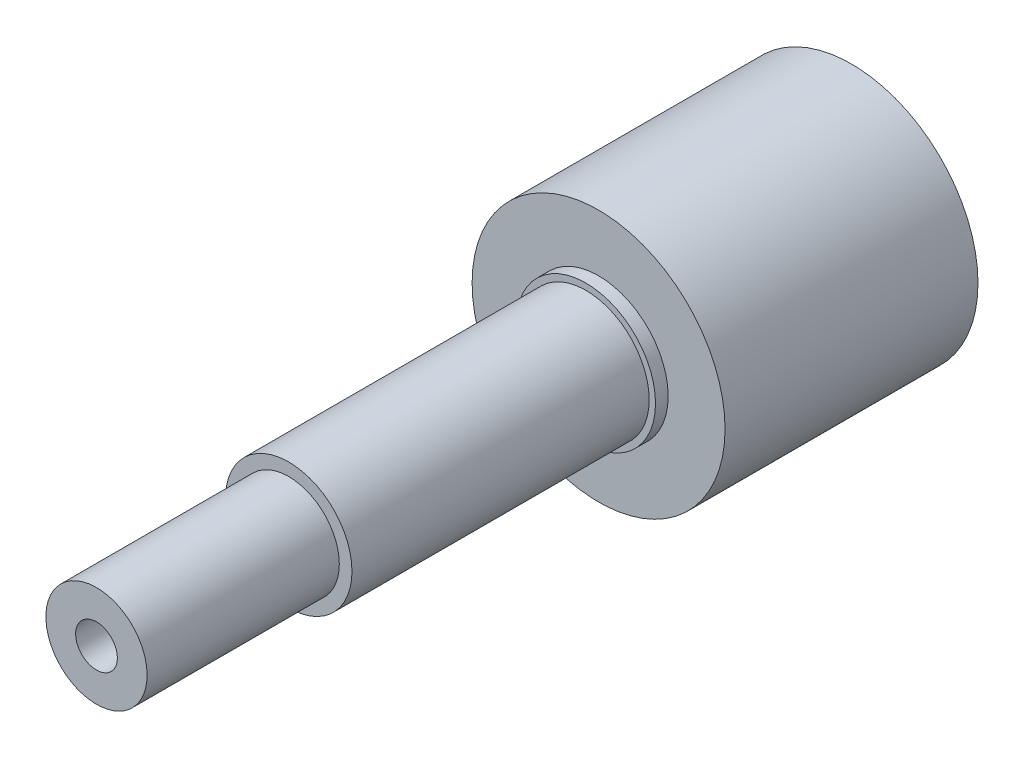
SolidWorks part; units mm, degrees
material "1060 合金"
ref_plane "正面" through (0, 0, 0) normal (0, 0, 1) x (1, 0, 0)
ref_plane "平面" through (0, 0, 0) normal (0, 1, 0) x (1, 0, 0)
ref_plane "右側面" through (0, 0, 0) normal (1, 0, 0) x (0, 0, -1)
sketch "ｽｹｯﾁ1" plane through (0, 0, 0) normal (0, 0, 1) x (1, 0, 0)
  circle A0 centre (0, 0) radius 10
  dimension "D1" = 20
extrude "ﾎﾞｽ - 押し出し1" add sketch "ｽｹｯﾁ1" along normal blind 20
sketch "ｽｹｯﾁ2" plane through (0, 0, 20) normal (0, 0, 1) x (1, 0, 0)
  circle A0 centre (0, 0) radius 5
  dimension "D1" = 10
extrude "ﾎﾞｽ - 押し出し2" add sketch "ｽｹｯﾁ2" along normal blind 5
sketch "ｽｹｯﾁ4" plane through (0, 0, 20) normal (0, 0, 1) x (1, 0, 0)
  circle A0 centre (0, 0) radius 5.5
  circle A1 centre (0, 0) radius 5
  dimension "D1" = 11
  dimension "D2" = 10
extrude "ﾎﾞｽ - 押し出し3" add sketch "ｽｹｯﾁ4" along normal blind 1
sketch "ｽｹｯﾁ5" plane through (0, 0, 0) normal (0, 0, -1) x (-1, 0, 0)
  line L0 (-10, 0) -> (10, 0) construction
  line L1 (0, -10) -> (0, 10) construction
  circle A0 centre (0, 0) radius 10 construction
  circle A1 centre (-8, 0) radius 1.65 construction
  circle A2 centre (8, 0) radius 1.65 construction
  circle A3 centre (0, 6) radius 1.65
  circle A4 centre (0, -6) radius 1.65
  circle A5 centre (0, 0) radius 1.65 construction
  dimension "D1" = 3.3
  dimension "D2" = 8
  dimension "D3" = 6
  dimension "D4" = 3.3
extrude "ｶｯﾄ - 押し出し1" cut sketch "ｽｹｯﾁ5" against normal blind 10
sketch "ｽｹｯﾁ6" plane through (0, 0, 25) normal (0, 0, 1) x (1, 0, 0)
  circle A0 centre (0, 0) radius 5
  dimension "D1" = 10
extrude "ﾎﾞｽ - 押し出し4" add sketch "ｽｹｯﾁ6" along normal blind 35.5
sketch "ｽｹｯﾁ7" plane through (0, 0, 60.5) normal (0, 0, 1) x (1, 0, 0)
  circle A0 centre (0, 0) radius 4
  dimension "D1" = 8
extrude "ｶｯﾄ - 押し出し2" cut sketch "ｽｹｯﾁ7" against normal blind 16 flip side to cut
sketch "ｽｹｯﾁ8" plane through (0, 0, 60.5) normal (0, 0, 1) x (1, 0, 0)
  circle A0 centre (0, 0) radius 1.65
  dimension "D1" = 3.3
extrude "ｶｯﾄ - 押し出し3" cut sketch "ｽｹｯﾁ8" against normal blind 10
sketch "ｽｹｯﾁ9" plane through (0, 0, 60.5) normal (0, 0, 1) x (1, 0, 0)
  circle A0 centre (0, 0) radius 4
  dimension "D1" = 8
extrude "ｶｯﾄ - 押し出し4" cut sketch "ｽｹｯﾁ9" against normal blind 0.8
